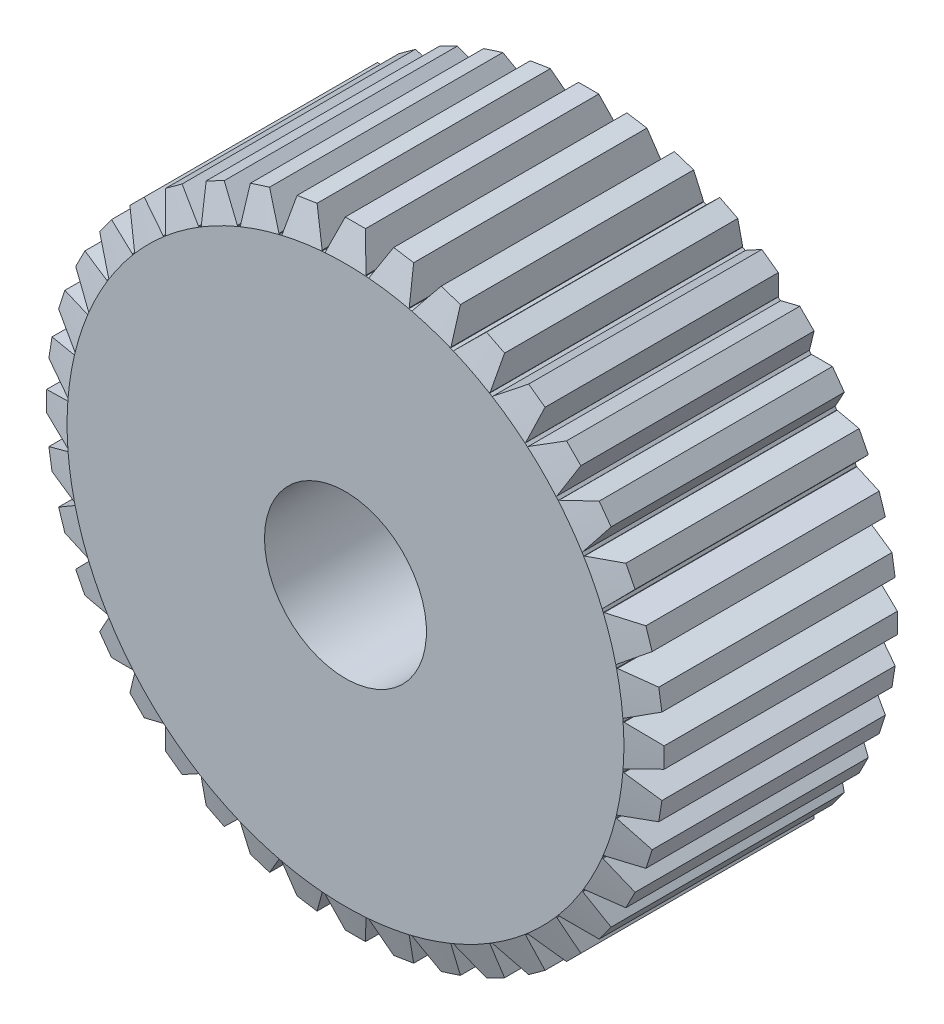
SolidWorks part; units mm, degrees
material "AISI 1020"
ref_plane "Front Plane" through (0, 0, 0) normal (0, 0, 1) x (1, 0, 0)
ref_plane "Top Plane" through (0, 0, 0) normal (0, 1, 0) x (1, 0, 0)
ref_plane "Right Plane" through (0, 0, 0) normal (1, 0, 0) x (0, 0, -1)
sketch "Sketch1" plane through (0, 0, 0) normal (0, 0, 1) x (1, 0, 0)
  circle A0 centre (0, 0) radius 6.985
  dimension "D1" = 13.97
extrude "Boss-Extrude1" add sketch "Sketch1" against normal blind 6.35
sketch "Sketch2" plane through (0, 0, 0) normal (0, 0, 1) x (1, 0, 0)
  line L2 (-0.508, 6.985) -> (-0.254, 7.747)
  line L3 (-0.254, 7.747) -> (0, 7.747)
  line L4 (0.508, 6.985) -> (0.254, 7.747)
  line L5 (0.254, 7.747) -> (0, 7.747)
  line L6 (-46.074, 6.985) -> (46.074, 6.985) construction
  line L8 (-0.508, 6.731) -> (0.508, 6.731)
  line L12 (-0.508, 6.985) -> (-0.508, 6.731)
  line L13 (0.508, 6.985) -> (0.508, 6.731)
  circle A0 centre (0, 0) radius 6.985 construction
  point P18 (0, 177.7274)
  dimension "D1" = 1.016
  dimension "D2" = 0.254
  dimension "D3" = 0.254
  dimension "D5" = 1.016
extrude "Boss-Extrude4" add sketch "Sketch2" against normal through all separate body contours L4 L5 L3 L2 L12 L8 L13
pattern_circular "CirPattern2" count 40 over 360 about axis through (0, 0, 0) along (0, 0, 1) of bodies 104
combine bodies "Combine2" bodies to combine 101 104 105 106 107 108 109 110 111 112 113 114 115 116 117 118 119 120 121 122 123 124 125 126 127 128 129 130 131 132 133 134 135 136 137 138 139 140 141 142
sketch "Sketch4" plane through (0, 0, 0) normal (1, 0, 0) x (0, 0, -1)
  line L5 (0, 0) -> (173.5338, 0) construction
  line L13 (6.096, 7.7667) -> (6.096, 8.001)
  line L14 (6.096, 8.001) -> (6.4008, 8.001)
  line L16 (6.4008, 6.985) -> (6.4008, 8.001)
  line L21 (6.096, 7.7667) -> (6.35, 6.985)
  line L22 (6.35, 6.985) -> (6.4008, 6.985)
  dimension "D1" = 0.3048
  dimension "D2" = 18
  dimension "D3" = 6.985
  dimension "D4" = 6.35
  dimension "D6" = 0.0508
ref_plane "Plane2" through (0, 0, -3.175) normal (0, 0, -1) x (-1, 0, 0)
sketch "Sketch5" plane through (0, 0, -6.35) normal (0, 0, -1) x (-1, 0, 0)
  circle A0 centre (0, 0) radius 4.318
  dimension "D1" = 8.636
extrude "Cut-Extrude1" cut sketch "Sketch5" against normal blind 1.778
sketch "Sketch6" plane through (0, 0, -4.572) normal (0, 0, -1) x (-1, 0, 0)
  circle A0 centre (0, 0) radius 2.667
  dimension "D1" = 5.334
revolve "Cut-Revolve3" cut sketch "Sketch4" angle 360 about L5
ref_plane "Plane3" through (0, 0, -3.175) normal (0, 0, 1) x (1, 0, 0)
mirror "Mirror1" about plane through (0, 0, -3.175) normal (0, 0, 1) of "Cut-Revolve3"
hole_wizard "#8-32 Tapped Hole1" positions "Sketch9" profile "Sketch10" tap size "#8-32" standard "ANSI Inch" end condition through all
sketch "Sketch9" plane through (0, 0, -4.572) normal (0, 0, -1) x (-1, 0, 0)
  point P0 (0, 0)
sketch "Sketch10" plane through (0, 0, -4.572) normal (1, 0, 0) x (0, 1, 0)
  line L0 (0, 0) -> (0, 4.572)
  line L1 (0, 4.572) -> (2.032, 4.572)
  line L2 (2.032, 4.572) -> (2.032, 0)
  line L5 (2.032, 0) -> (0, 0)
  line L11 (0, -6.35) -> (0, 107.95) construction
  dimension "Thru Tap Drill Dia." = 4.064
  dimension "Thru Tap Drill Depth" = 4.572
cosmetic thread "Hole Thread1" parameters "D2"=4.1656
